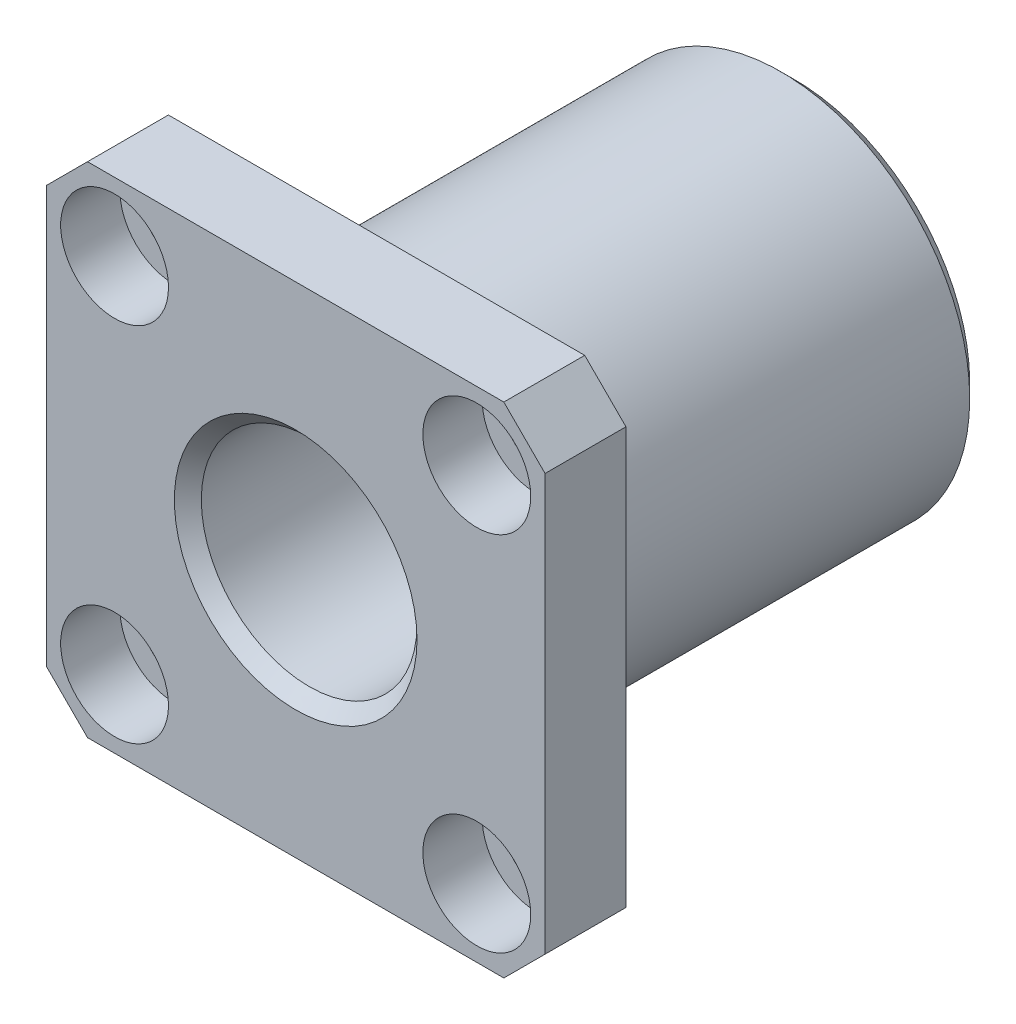
SolidWorks part; units mm, degrees
ref_plane "Front Plane" through (0, 0, 0) normal (0, 0, 1) x (1, 0, 0)
ref_plane "Top Plane" through (0, 0, 0) normal (0, 1, 0) x (1, 0, 0)
ref_plane "Right Plane" through (0, 0, 0) normal (1, 0, 0) x (0, 0, -1)
sketch "Sketch1" plane through (0, 0, 0) normal (0, 0, 1) x (1, 0, 0)
  circle A0 centre (0, 0) radius 14
  dimension "D1" = 28
extrude "Boss-Extrude1" add sketch "Sketch1" along normal blind 37
sketch "Sketch2" plane through (0, 0, 37) normal (0, 0, 1) x (1, 0, 0)
  line L1 (-18.5, -18.5) -> (18.5, -18.5)
  line L2 (-18.5, -18.5) -> (-18.5, 18.5)
  line L3 (-18.5, 18.5) -> (18.5, 18.5)
  line L4 (18.5, -18.5) -> (18.5, 18.5)
  line L5 (-18.5, -18.5) -> (18.5, 18.5) construction
  line L6 (-18.5, 18.5) -> (18.5, -18.5) construction
  point P0 (0, 0)
  dimension "D1" = 37
extrude "Boss-Extrude2" add sketch "Sketch2" against normal blind 6
sketch "Sketch4" plane through (0, 0, 37) normal (0, 0, 1) x (1, 0, 0)
  line L0 (0, 18.5) -> (0, -18.5) construction
  line L1 (18.5, 18.5) -> (-18.5, 18.5) construction
  line L2 (-18.5, -18.5) -> (18.5, -18.5) construction
  line L3 (-18.5, 18.5) -> (-18.5, 15.4411)
  line L4 (-18.5, 18.5) -> (-18.5, -18.5) construction
  line L5 (-18.5, 15.4411) -> (-15.4411, 18.5)
  line L6 (-15.4411, 18.5) -> (-18.5, 18.5)
  line L7 (15.4411, 18.5) -> (18.5, 18.5)
  line L8 (18.5, 15.4411) -> (15.4411, 18.5)
  line L9 (18.5, 18.5) -> (18.5, 15.4411)
  line L10 (-18.5, 0) -> (18.5, 0) construction
  line L11 (18.5, -18.5) -> (18.5, 18.5) construction
  line L12 (18.5, -18.5) -> (18.5, -15.4411)
  line L13 (18.5, -15.4411) -> (15.4411, -18.5)
  line L14 (15.4411, -18.5) -> (18.5, -18.5)
  line L15 (-15.4411, -18.5) -> (-18.5, -18.5)
  line L16 (-18.5, -15.4411) -> (-15.4411, -18.5)
  line L17 (-18.5, -18.5) -> (-18.5, -15.4411)
  dimension "D1" = 48
extrude "Cut-Extrude1" cut sketch "Sketch4" against normal through all
sketch "Sketch5" plane through (0, 0, 37) normal (0, 0, 1) x (1, 0, 0)
  line L0 (0, 0) -> (-16.9706, 16.9706) construction
  line L1 (-18.5, 15.4411) -> (-15.4411, 18.5) construction
  circle A0 centre (0, 0) radius 19 construction
  point P6 (-13.435, 13.435)
  point P10 (13.435, 13.435)
  point P11 (13.435, -13.435)
  point P12 (-13.435, -13.435)
  point P13 (0, 0)
  dimension "D1" = 38
  dimension "D2" = 4
hole_wizard "CBORE for M4 Hex Socket Head Cap Screw1" positions "Sketch6" profile "Sketch7" counterbore size "M4" standard "ISO"
sketch "Sketch6" plane through (0, 0, 37) normal (0, 0, 1) x (1, 0, 0)
  point P0 (-13.435, 13.435)
  point P3 (13.435, 13.435)
  point P6 (13.435, -13.435)
  point P9 (-13.435, -13.435)
sketch "Sketch7" plane through (-13.435, 13.435, 37) normal (1, 0, 0) x (0, -1, 0)
  line L0 (0, 0) -> (0, 23.3519)
  line L1 (0, 23.3519) -> (2.25, 22)
  line L2 (2.25, 22) -> (2.25, 4.4)
  line L3 (2.25, 4.4) -> (4, 4.4)
  line L4 (4, 4.4) -> (4, 0)
  line L5 (4, 0) -> (0, 0)
  line L10 (0, 23.3519) -> (-2.25, 22) construction
  line L11 (0, -6.35) -> (0, 107.95) construction
  dimension "Hole Dia." = 4.5
  dimension "Hole Depth" = 22
  dimension "C'Bore Dia." = 8
  dimension "C'Bore Depth" = 4.4
  dimension "Drill Angle" = 118
sketch "Sketch8" plane through (0, 0, 37) normal (0, 0, 1) x (1, 0, 0)
  circle A0 centre (0, 0) radius 8
  dimension "D1" = 16
extrude "Cut-Extrude2" cut sketch "Sketch8" against normal through all
chamfer "Chamfer1" distance 1 angle 45 2 edges at (14, 0, 0) (8, 0, 37)
